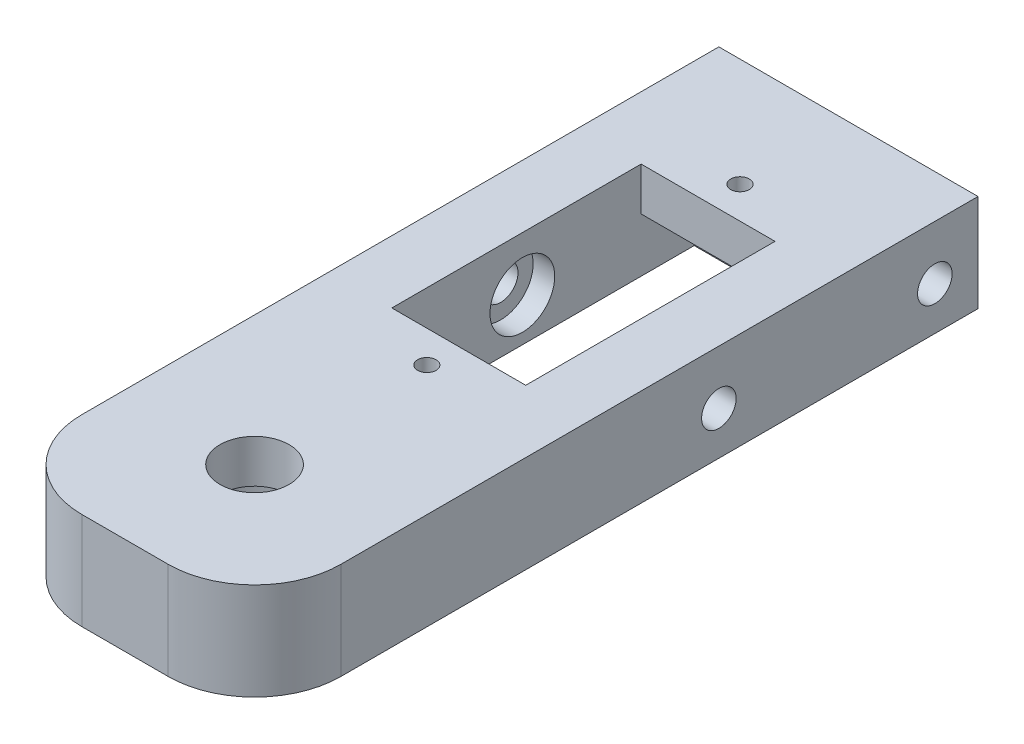
SolidWorks part; units mm, degrees
ref_plane "前视基准面" through (0, 0, 0) normal (0, 0, 1) x (1, 0, 0)
ref_plane "上视基准面" through (0, 0, 0) normal (0, 1, 0) x (1, 0, 0)
ref_plane "右视基准面" through (0, 0, 0) normal (1, 0, 0) x (0, 0, -1)
sketch "草图1" plane through (0, 0, 0) normal (1, 0, 0) x (0, 0, -1)
  line L1 (55, -4) -> (-12, -4)
  line L2 (55, -4) -> (55, 5)
  line L3 (55, 5) -> (-12, 5)
  line L4 (-12, -4) -> (-12, 5)
  line L5 (55, -4) -> (-12, 5) construction
  line L6 (55, 5) -> (-12, -4) construction
  point P0 (21.5, 0.5)
  point P5 (0, 0)
  point P6 (0, 0)
extrude "凸台-拉伸1" add sketch "草图1" along normal mid plane 24
sketch "草图2" plane through (0, -4, 0) normal (0, 1, 0) x (1, 0, 0)
  circle A0 centre (0, 0) radius 6.7
extrude "切除-拉伸1" cut sketch "草图2" along normal blind 5
sketch "草图4" plane through (0, 1, 0) normal (0, -1, 0) x (1, 0, 0)
  circle A0 centre (0, 0) radius 3.2
extrude "切除-拉伸3" cut sketch "草图4" against normal through all
sketch "草图3" plane through (0, 5, 0) normal (0, 1, 0) x (1, 0, 0)
  line L1 (6.2, 42) -> (-6.2, 42)
  line L2 (6.2, 42) -> (6.2, 18.9147)
  line L3 (6.2, 18.9147) -> (-6.2, 18.9147)
  line L4 (-6.2, 42) -> (-6.2, 18.9147)
  line L5 (6.2, 42) -> (-6.2, 18.9147) construction
  line L6 (6.2, 18.9147) -> (-6.2, 42) construction
  point P0 (0, 30.4574)
extrude "切除-拉伸2" cut sketch "草图3" against normal through all
sketch "草图5" plane through (0, -4, 0) normal (0, -1, 0) x (1, 0, 0)
  line L1 (6.2, -46.9147) -> (-6.2, -46.9147)
  line L2 (6.2, -46.9147) -> (6.2, -14)
  line L3 (6.2, -14) -> (-6.2, -14)
  line L4 (-6.2, -46.9147) -> (-6.2, -14)
  line L5 (6.2, -46.9147) -> (-6.2, -14) construction
  line L6 (6.2, -14) -> (-6.2, -46.9147) construction
  line L7 (-6.2, -42) -> (-6.2, -18.9147) construction
  line L8 (-6.2, -18.9147) -> (6.2, -18.9147) construction
  point P0 (0, -30.4574)
  point P8 (-6.2, -30.4574)
  point P11 (0, -18.9147)
extrude "切除-拉伸4" cut sketch "草图5" against normal offset from surface (5 mm away) 4 up to face at (0, 5, -30.4574)
sketch "草图6" plane through (0, 1, 0) normal (0, -1, 0) x (1, 0, 0)
  line L0 (-6.2, -30.4574) -> (6.2, -30.4574) construction
  line L1 (-6.2, -46.9147) -> (-6.2, -14) construction
  line L2 (6.2, -14) -> (6.2, -46.9147) construction
  line L3 (0, -30.4574) -> (0, -15.9574) construction
  circle A0 centre (0, -15.9574) radius 0.8555
  circle A2 centre (0, -44.9574) radius 0.8555
extrude "切除-拉伸5" cut sketch "草图6" against normal through all
fillet "圆角1" radius 8 2 edges at (-12, 0.5, 12) (12, 0.5, 12)
sketch "草图7" plane through (12, 0, 0) normal (1, 0, 0) x (0, 0, -1)
  line L0 (31.0016, 0) -> (51.0016, 0) construction
  circle A0 centre (51.0016, 0) radius 1.6
  circle A1 centre (31.0016, 0) radius 1.6
  point P4 (0, 0)
extrude "切除-拉伸6" cut sketch "草图7" against normal through all
sketch "草图8" plane through (-6.2, 0, 0) normal (1, 0, 0) x (0, 0, -1)
  circle A0 centre (31.0016, 0) radius 3
extrude "切除-拉伸7" cut sketch "草图8" against normal blind 2
mirror "镜向1" about plane through (0, 0, 0) normal (1, 0, 0) of "切除-拉伸7"
